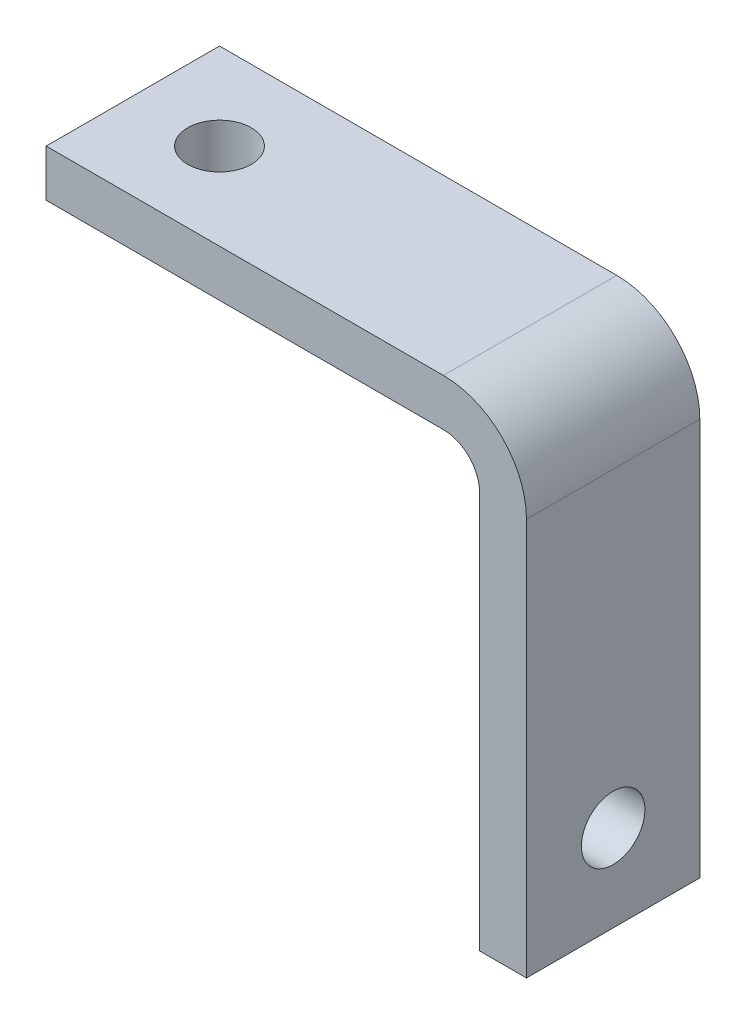
SolidWorks part; units mm, degrees
material "1060 Alloy"
ref_plane "Front Plane" through (0, 0, 0) normal (0, 0, 1) x (1, 0, 0)
ref_plane "Top Plane" through (0, 0, 0) normal (0, 1, 0) x (1, 0, 0)
ref_plane "Right Plane" through (0, 0, 0) normal (1, 0, 0) x (0, 0, -1)
sketch "Sketch1" plane through (0, 0, 0) normal (0, 1, 0) x (1, 0, 0)
  line L1 (0, 0) -> (-33.25, 0)
  line L2 (0, 0) -> (0, 12)
  line L3 (0, 12) -> (-33.25, 12)
  line L4 (-33.25, 0) -> (-33.25, 12)
  dimension "D1" = 12
  dimension "D2" = 33.25
extrude "Boss-Extrude1" add sketch "Sketch1" along normal blind 3.25
sketch "Sketch2" plane through (0, 3.25, 0) normal (0, 1, 0) x (1, 0, 0)
  line L0 (-33.25, 12) -> (-21.25, 12) construction
  line L1 (0, 12) -> (-33.25, 12) construction
  line L2 (-27.25, 12) -> (-27.25, 0) construction
  line L3 (-33.25, 0) -> (0, 0) construction
  circle A0 centre (-27.25, 6) radius 2.2
  dimension "D2" = 4.4
  dimension "D1" = 12
extrude "Cut-Extrude1" cut sketch "Sketch2" against normal through all and the other way through all
sketch "Sketch3" plane through (0, 0, 0) normal (0, -1, 0) x (1, 0, 0)
  line L0 (0, -12) -> (-33.25, -12) construction
  line L1 (0, 0) -> (-3.25, 0)
  line L2 (0, 0) -> (0, -12)
  line L3 (0, -12) -> (-3.25, -12)
  line L4 (-3.25, 0) -> (-3.25, -12)
  dimension "D1" = 3.25
extrude "Boss-Extrude2" add sketch "Sketch3" along normal blind 30
sketch "Sketch4" plane through (0, 0, 0) normal (1, 0, 0) x (0, 0, -1)
  line L1 (12, -30) -> (0, -30) construction
  line L3 (0, -10.375) -> (12, -10.375) construction
  line L6 (6, -18) -> (6, -30) construction
  circle A0 centre (6, -24) radius 2.2
  point P5 (0, 0)
  point P10 (0, 0)
  dimension "D1" = 4.4
  dimension "D2" = 12
extrude "Cut-Extrude2" cut sketch "Sketch4" against normal through all
fillet "Fillet2" radius 5.75 1 edges at (0, 3.25, -6)
fillet "Fillet3" radius 2.5 1 edges at (-3.25, 0, -6)
